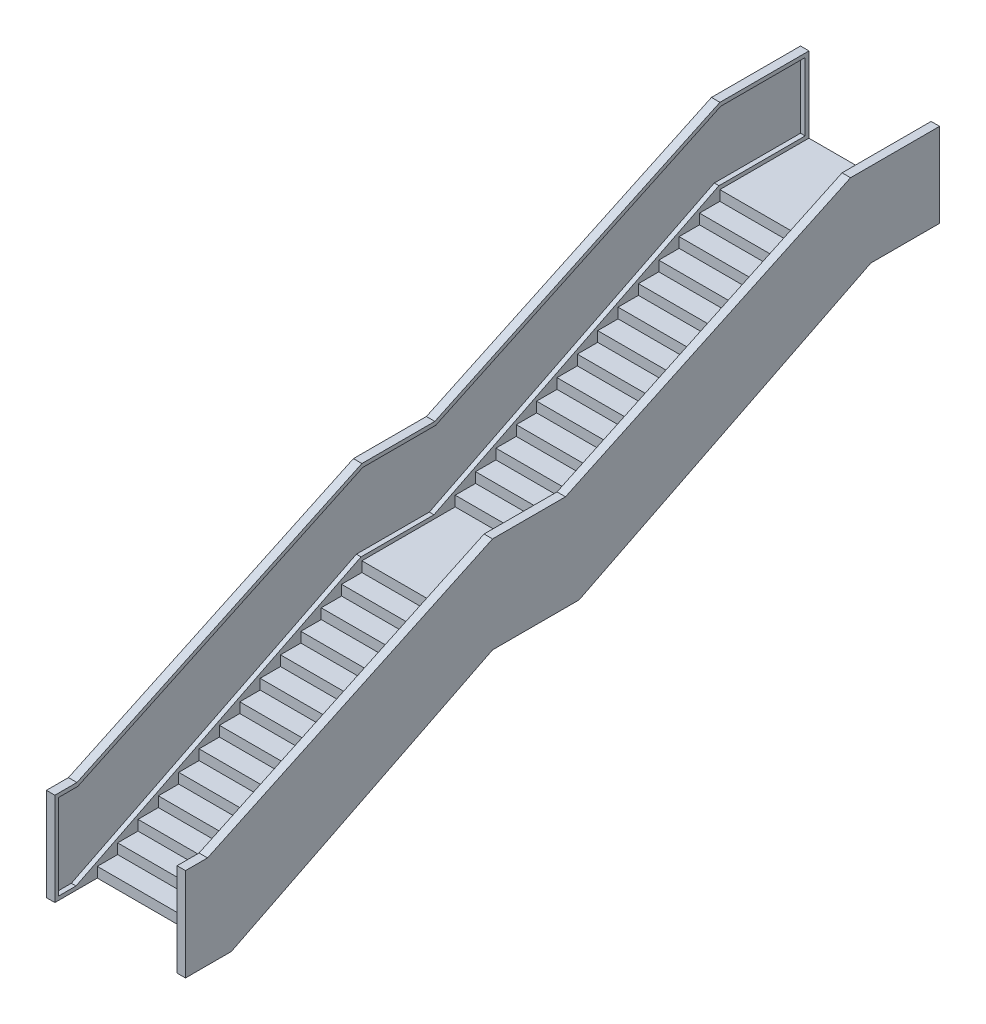
SolidWorks part; units mm, degrees
ref_plane "Front Plane" through (0, 0, 0) normal (0, 0, 1) x (1, 0, 0)
ref_plane "Top Plane" through (0, 0, 0) normal (0, 1, 0) x (1, 0, 0)
ref_plane "Right Plane" through (0, 0, 0) normal (1, 0, 0) x (0, 0, -1)
sketch "Sketch1" plane through (0, 0, 0) normal (1, 0, 0) x (0, 0, -1)
  line L0 (4267.2, 0) -> (4267.2, -2133.6)
  line L2 (4267.2, 2133.6) -> (4680.1394, 2133.6)
  line L3 (4267.2, 2133.6) -> (3962.4, 2133.6)
  line L4 (3962.4, 2133.6) -> (3962.4, 1981.2)
  line L5 (3962.4, 1981.2) -> (3657.6, 1981.2)
  line L6 (3657.6, 1981.2) -> (3657.6, 1828.8)
  line L7 (3657.6, 1828.8) -> (3352.8, 1828.8)
  line L8 (3352.8, 1828.8) -> (3352.8, 1676.4)
  line L9 (3352.8, 1676.4) -> (3048, 1676.4)
  line L10 (3048, 1676.4) -> (3048, 1524)
  line L11 (3048, 1524) -> (2743.2, 1524)
  line L12 (2743.2, 1524) -> (2743.2, 1371.6)
  line L13 (2743.2, 1371.6) -> (2438.4, 1371.6)
  line L14 (2438.4, 1371.6) -> (2438.4, 1219.2)
  line L15 (2438.4, 1219.2) -> (2133.6, 1219.2)
  line L16 (2133.6, 1219.2) -> (2133.6, 1066.8)
  line L17 (2133.6, 1066.8) -> (1828.8, 1066.8)
  line L18 (1828.8, 1066.8) -> (1828.8, 914.4)
  line L19 (1828.8, 914.4) -> (1524, 914.4)
  line L20 (1524, 914.4) -> (1524, 762)
  line L21 (1524, 762) -> (1219.2, 762)
  line L22 (1219.2, 762) -> (1219.2, 609.6)
  line L23 (1219.2, 609.6) -> (914.4, 609.6)
  line L24 (914.4, 609.6) -> (914.4, 457.2)
  line L25 (914.4, 457.2) -> (609.6, 457.2)
  line L26 (609.6, 457.2) -> (609.6, 304.8)
  line L27 (609.6, 304.8) -> (304.8, 304.8)
  line L28 (304.8, 304.8) -> (304.8, 152.4)
  line L29 (304.8, 152.4) -> (0, 152.4)
  line L30 (0, 152.4) -> (0, 0)
  line L31 (4267.2, 2133.6) -> (4267.2, 0)
  line L33 (0, 0) -> (-1397, 0)
  line L35 (-1397, 0) -> (-1397, -152.4)
  line L36 (-1397, -152.4) -> (-1701.8, -152.4)
  line L37 (-1701.8, -152.4) -> (-1701.8, -304.8)
  line L38 (-1701.8, -304.8) -> (-2006.6, -304.8)
  line L39 (-2006.6, -304.8) -> (-2006.6, -457.2)
  line L40 (-2006.6, -457.2) -> (-2311.4, -457.2)
  line L41 (-2311.4, -457.2) -> (-2311.4, -609.6)
  line L42 (-2311.4, -609.6) -> (-2616.2, -609.6)
  line L43 (-2616.2, -609.6) -> (-2616.2, -762)
  line L44 (-2616.2, -762) -> (-2921, -762)
  line L45 (-2921, -762) -> (-2921, -914.4)
  line L46 (-2921, -914.4) -> (-3225.8, -914.4)
  line L47 (-3225.8, -914.4) -> (-3225.8, -1066.8)
  line L48 (-3225.8, -1066.8) -> (-3530.6, -1066.8)
  line L49 (-3530.6, -1066.8) -> (-3530.6, -1219.2)
  line L50 (-3530.6, -1219.2) -> (-3835.4, -1219.2)
  line L51 (-3835.4, -1219.2) -> (-3835.4, -1371.6)
  line L52 (-3835.4, -1371.6) -> (-4140.2, -1371.6)
  line L53 (-4140.2, -1371.6) -> (-4140.2, -1524)
  line L54 (-4140.2, -1524) -> (-4445, -1524)
  line L55 (-4445, -1524) -> (-4445, -1676.4)
  line L56 (-4445, -1676.4) -> (-4749.8, -1676.4)
  line L57 (-4749.8, -1676.4) -> (-4749.8, -1828.8)
  line L58 (-4749.8, -1828.8) -> (-5054.6, -1828.8)
  line L59 (-5054.6, -1828.8) -> (-5054.6, -1981.2)
  line L61 (-5359.4, -2133.6) -> (4267.2, -2133.6)
  line L63 (-5054.6, -1981.2) -> (-5359.4, -1981.2)
  line L65 (-5359.4, -1981.2) -> (-5359.4, -2133.6)
  dimension "D3" = 152.4
  dimension "D4" = 152.4
  dimension "D5" = 152.4
  dimension "D6" = 152.4
  dimension "D7" = 152.4
  dimension "D8" = 152.4
  dimension "D9" = 152.4
  dimension "D10" = 152.4
  dimension "D11" = 152.4
  dimension "D12" = 152.4
  dimension "D13" = 152.4
  dimension "D14" = 152.4
  dimension "D15" = 152.4
  dimension "D16" = 2133.6
  dimension "D17" = 1397
  dimension "D18" = 2133.6
  dimension "D19" = 152.4
  dimension "D20" = 152.4
  dimension "D21" = 152.4
  dimension "D22" = 152.4
  dimension "D23" = 152.4
  dimension "D24" = 152.4
  dimension "D25" = 152.4
  dimension "D26" = 152.4
  dimension "D27" = 152.4
  dimension "D28" = 152.4
  dimension "D29" = 152.4
  dimension "D30" = 152.4
  dimension "D31" = 152.4
  dimension "D32" = 304.8
  dimension "D33" = 304.8
extrude "Boss-Extrude1" add sketch "Sketch1" along normal blind 1828.8
sketch "Sketch3" plane through (1828.8, 0, 0) normal (1, 0, 0) x (0, 0, -1)
  line L0 (4267.2, 2133.6) -> (6157.6252, 2133.6) construction
  line L1 (-1397, 0) -> (-3168.5559, 0) construction
  line L2 (-5359.4, -2133.6) -> (-6997.1987, -2133.6) construction
  line L4 (-5994.4, -741.186) -> (-5664.2, -741.186)
  line L5 (-5664.2, -741.186) -> (-1397, 1261.4887)
  line L6 (-1397, 1261.4887) -> (-304.8, 1261.4887)
  line L7 (-304.8, 1261.4887) -> (3963.7558, 3264.7997)
  line L8 (3963.7558, 3264.7997) -> (5297.2558, 3264.7997)
  line L9 (5297.2558, 3264.7997) -> (5297.2558, 2133.6)
  line L10 (5297.2558, 2133.6) -> (4267.2, 2133.6)
  line L30 (0, 152.4) -> (0, 0) construction
  line L69 (3962.4, 2133.6) -> (4267.2, 2133.6)
  line L72 (-304.8, 0) -> (-1397, 0)
  line L73 (3962.4, 2133.6) -> (-304.8, 0)
  line L75 (-5664.2, -2133.6) -> (-5994.4, -2133.6)
  line L76 (-5994.4, -2133.6) -> (-5994.4, -741.186)
  line L82 (-1397, 0) -> (-5664.2, -2133.6)
  dimension "D1" = 1333.5
  dimension "D2" = 330.2
  dimension "D3" = 304.8
  dimension "D4" = 304.8
extrude "Boss-Extrude4" add sketch "Sketch3" along normal blind 127 separate body
sketch "Sketch4" plane through (0, 0, 0) normal (-1, 0, 0) x (0, 0, 1)
  line L83 (-3962.4, 2133.6) -> (304.8, 0)
  line L84 (-3962.4, 2133.6) -> (304.8, 0)
  line L85 (-5297.2558, 2133.6) -> (-3962.4, 2133.6)
  line L86 (1397, 0) -> (5664.2, -2133.6)
  line L87 (1397, 0) -> (5664.2, -2133.6)
  line L88 (304.8, 0) -> (1397, 0)
  line L91 (5664.2, -2133.6) -> (5994.4, -2133.6)
  line L92 (5994.4, -2133.6) -> (5994.4, -741.186)
  line L93 (5994.4, -741.186) -> (5664.2, -741.186)
  line L94 (5664.2, -741.186) -> (1397, 1261.4887)
  line L95 (1397, 1261.4887) -> (304.8, 1261.4887)
  line L96 (304.8, 1261.4887) -> (-3963.7558, 3264.7997)
  line L97 (-3963.7558, 3264.7997) -> (-5297.2558, 3264.7997)
  line L98 (-5297.2558, 3264.7997) -> (-5297.2558, 2133.6)
  line L99 (-5297.2558, 2133.6) -> (-3962.4, 2133.6)
  line L102 (304.8, 0) -> (1397, 0)
  line L105 (5664.2, -2133.6) -> (5994.4, -2133.6)
  line L106 (5994.4, -2133.6) -> (5994.4, -741.186)
  line L107 (5994.4, -741.186) -> (5664.2, -741.186)
  line L108 (5664.2, -741.186) -> (1397, 1261.4887)
  line L109 (1397, 1261.4887) -> (304.8, 1261.4887)
  line L110 (304.8, 1261.4887) -> (-3963.7558, 3264.7997)
  line L111 (-3963.7558, 3264.7997) -> (-5297.2558, 3264.7997)
  line L112 (-5297.2558, 3264.7997) -> (-5297.2558, 2133.6)
  dimension "D1" = 0
extrude "Boss-Extrude15" add sketch "Sketch4" along normal blind 127 separate body
sketch "Sketch10" plane through (0, 0, 0) normal (-1, 0, 0) x (0, 0, 1)
  line L0 (-4267.2, 2133.6) -> (-3962.4, 2133.6)
  line L1 (-3962.4, 2133.6) -> (-3962.4, 1981.2)
  line L2 (-3962.4, 1981.2) -> (0, 0)
  line L3 (0, 0) -> (1397, 0)
  line L4 (1397, 0) -> (1397, -152.4)
  line L5 (1397, -152.4) -> (5359.4, -2133.6)
  line L6 (5359.4, -2133.6) -> (5308.6, -2133.6)
  line L7 (5359.4, -2133.6) -> (-4267.2, -2133.6) construction
  line L8 (5308.6, -2133.6) -> (1397, -177.8)
  line L9 (1397, -177.8) -> (101.6, -177.8)
  line L10 (101.6, -177.8) -> (-4267.2, 2006.6)
  line L11 (-4267.2, 2133.6) -> (-4267.2, -2133.6) construction
  line L12 (-4267.2, 2006.6) -> (-4267.2, 2133.6)
  line L13 (-4267.2, 2006.6) -> (-4267.2, -2133.6)
  line L14 (-4267.2, -2133.6) -> (5308.6, -2133.6)
  dimension "D1" = 127
  dimension "D2" = 25.4
extrude "Cut-Extrude2" cut sketch "Sketch10" against normal through all both and the other way through all contours L13 L14 L8 L9 L10
shell "Shell1" thickness 2.54
sketch "Sketch11" plane through (0, 0, -4267.2) normal (0, 0, -1) x (-1, 0, 0)
  line L1 (-1828.8, 2133.6) -> (0, 2133.6)
  line L2 (-1828.8, 2133.6) -> (-1828.8, 2006.6)
  line L3 (-1828.8, 2006.6) -> (0, 2006.6)
  line L4 (0, 2133.6) -> (0, 2006.6)
extrude "Boss-Extrude16" add sketch "Sketch11" along normal blind 1028.7
shell "Shell2" thickness 57.15
shell "Shell3" thickness 57.15
sketch "Sketch17" plane through (1955.8, 0, 0) normal (1, 0, 0) x (0, 0, -1)
  line L0 (5295.9, 2133.6) -> (5295.9, 2006.6)
  line L1 (5295.9, 2006.6) -> (4267.2, 2006.6)
  line L2 (4267.2, 2006.6) -> (-101.6, -177.8)
  line L3 (-101.6, -177.8) -> (-1397, -177.8)
  line L4 (-1397, -177.8) -> (-5308.6, -2133.6)
  line L5 (-5308.6, -2133.6) -> (-5664.2, -2133.6)
  line L6 (-5664.2, -2133.6) -> (-1397, 0)
  line L7 (5295.9, 2133.6) -> (3962.4, 2133.6)
  line L8 (3962.4, 2133.6) -> (-304.8, 0)
  line L9 (-304.8, 0) -> (-1397, 0)
extrude "Boss-Extrude20" add sketch "Sketch17" against normal blind 127
sketch "Sketch20" plane through (-127, 0, 0) normal (-1, 0, 0) x (0, 0, 1)
  line L0 (-5297.2558, 2133.6) -> (-3962.4, 2133.6)
  line L1 (-3962.4, 2133.6) -> (304.8, 0)
  line L2 (304.8, 0) -> (1397, 0)
  line L3 (1397, 0) -> (5664.2, -2133.6)
  line L4 (5664.2, -2133.6) -> (5308.6, -2133.6)
  line L5 (5308.6, -2133.6) -> (1397, -177.8)
  line L6 (1397, -177.8) -> (101.6, -177.8)
  line L7 (101.6, -177.8) -> (-4267.2, 2006.6)
  line L8 (-4267.2, 2006.6) -> (-5295.9, 2006.6)
  line L9 (-5295.9, 2006.6) -> (-5297.2558, 2133.6)
extrude "Boss-Extrude21" add sketch "Sketch20" against normal blind 127
ref_plane "Plane1" through (1898.65, 0, 0) normal (-1, 0, 0) x (0, 0, 1)
sketch "Sketch8" plane through (1898.65, 0, 0) normal (-1, 0, 0) x (0, 0, 1)
  line L8 (5715, -1949.45) -> (1398.4944, 208.8028)
  line L9 (1398.4944, 208.8028) -> (1400.7662, 213.3465)
  line L10 (1400.7662, 213.3465) -> (5717.2718, -1944.9063)
  line L12 (5717.2718, -1944.9063) -> (5715, -1949.45)
  line L13 (1399.6303, 211.0747) -> (5716.1359, -1947.1782) construction
  line L15 (5207, -1981.2) -> (5323.5718, -1748.0563) construction
  line L16 (5054.6, -1981.2) -> (5359.4, -1981.2) construction
  line L18 (4597.4, -1676.4) -> (4713.9718, -1443.2563) construction
  line L19 (4445, -1676.4) -> (4749.8, -1676.4) construction
  line L20 (3987.8, -1371.6) -> (4104.3718, -1138.4563) construction
  line L21 (3835.4, -1371.6) -> (4140.2, -1371.6) construction
  line L22 (3378.2, -1066.8) -> (3494.7718, -833.6563) construction
  line L23 (3225.8, -1066.8) -> (3530.6, -1066.8) construction
  line L24 (2768.6, -762) -> (2885.1718, -528.8563) construction
  line L25 (2616.2, -762) -> (2921, -762) construction
  line L26 (2159, -457.2) -> (2275.5718, -224.0563) construction
  line L27 (2006.6, -457.2) -> (2311.4, -457.2) construction
  line L28 (1549.4, -152.4) -> (1665.9718, 80.7437) construction
  line L29 (1397, -152.4) -> (1701.8, -152.4) construction
  line L30 (5677.6913, -2076.45) -> (1410.4913, 57.15) construction
  line L31 (265.9134, 314.5101) -> (-3937, 2415.9668)
  line L32 (-152.4, 152.4) -> (-3.8933, 449.4134) construction
  line L33 (-304.8, 152.4) -> (0, 152.4) construction
  line L34 (-762, 457.2) -> (-613.4933, 754.2134) construction
  line L35 (-914.4, 457.2) -> (-609.6, 457.2) construction
  line L36 (-1371.6, 762) -> (-1223.0933, 1059.0134) construction
  line L37 (-1524, 762) -> (-1219.2, 762) construction
  line L38 (-1981.2, 1066.8) -> (-1832.6933, 1363.8134) construction
  line L39 (-2133.6, 1066.8) -> (-1828.8, 1066.8) construction
  line L40 (-2590.8, 1371.6) -> (-2442.2933, 1668.6134) construction
  line L41 (-2743.2, 1371.6) -> (-2438.4, 1371.6) construction
  line L42 (-3200.4, 1676.4) -> (-3051.8933, 1973.4134) construction
  line L43 (-3352.8, 1676.4) -> (-3048, 1676.4) construction
  line L44 (-3810, 1981.2) -> (-3661.4933, 2278.2134) construction
  line L45 (-3962.4, 1981.2) -> (-3657.6, 1981.2) construction
  line L46 (265.9134, 314.5101) -> (268.1852, 319.0538)
  line L47 (268.1852, 319.0538) -> (-3934.7282, 2420.5105)
  line L48 (-3934.7282, 2420.5105) -> (-3937, 2415.9668)
  point P38 (5716.1359, -1947.1782)
  dimension "D2" = 4826
  dimension "D3" = 279.4
  dimension "D5" = 127
  dimension "D6" = 440.17
  dimension "D7" = 1121.7235
  dimension "D8" = 1803.277
  dimension "D9" = 2484.8305
  dimension "D10" = 3166.3841
  dimension "D11" = 3847.9376
  dimension "D12" = 4529.4911
  dimension "D13" = 5.08
  dimension "D15" = 262.636
  dimension "D16" = 4699
  dimension "D17" = 25.4
  dimension "D18" = 5.08
extrude "Boss-Extrude22" add sketch "Sketch8" along normal blind 57.15
